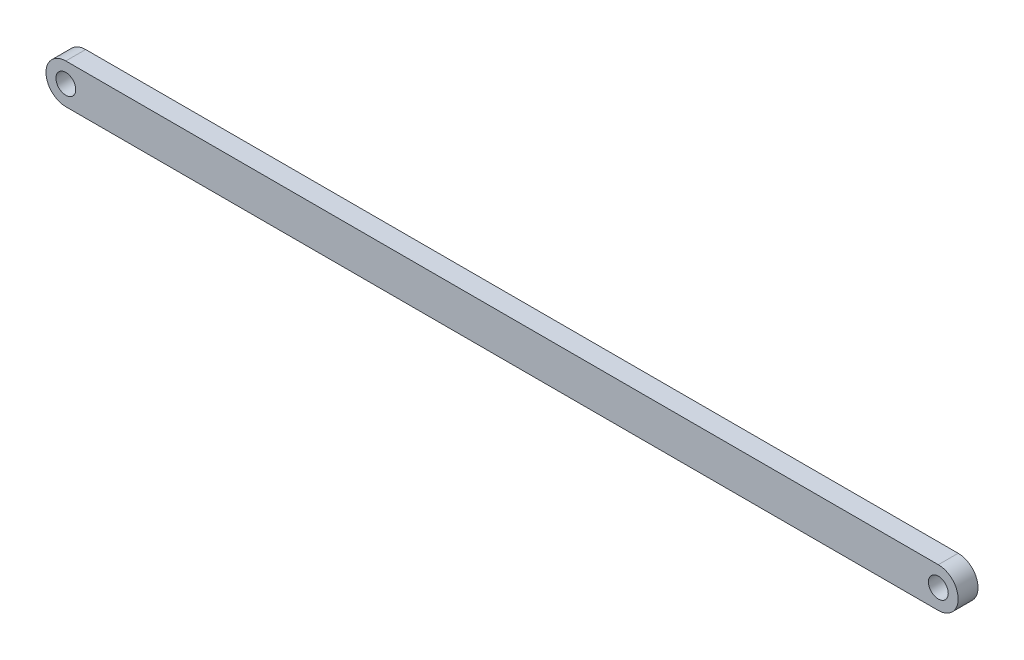
SolidWorks part; units mm, degrees
ref_plane "前视基准面" through (0, 0, 0) normal (0, 0, 1) x (1, 0, 0)
ref_plane "上视基准面" through (0, 0, 0) normal (0, 1, 0) x (1, 0, 0)
ref_plane "右视基准面" through (0, 0, 0) normal (1, 0, 0) x (0, 0, -1)
other "Configuration Table"
sketch "草图1" plane through (0, 0, 0) normal (0, 0, 1) x (1, 0, 0)
  line L0 (0, 5) -> (220, 5)
  line L1 (0, -5) -> (220, -5)
  circle A0 centre (0, 0) radius 2.5
  arc A1 (0, 5) -> (0, -5) centre (0, 0) ccw
  arc A4 (220, -5) -> (220, 5) centre (220, 0) ccw
  circle A5 centre (220, 0) radius 2.5
  dimension "D2" = 5
  dimension "D3" = 5
  dimension "D4" = 5
  dimension "D1" = 220
extrude "凸台-拉伸4" add sketch "草图1" along normal blind 5
